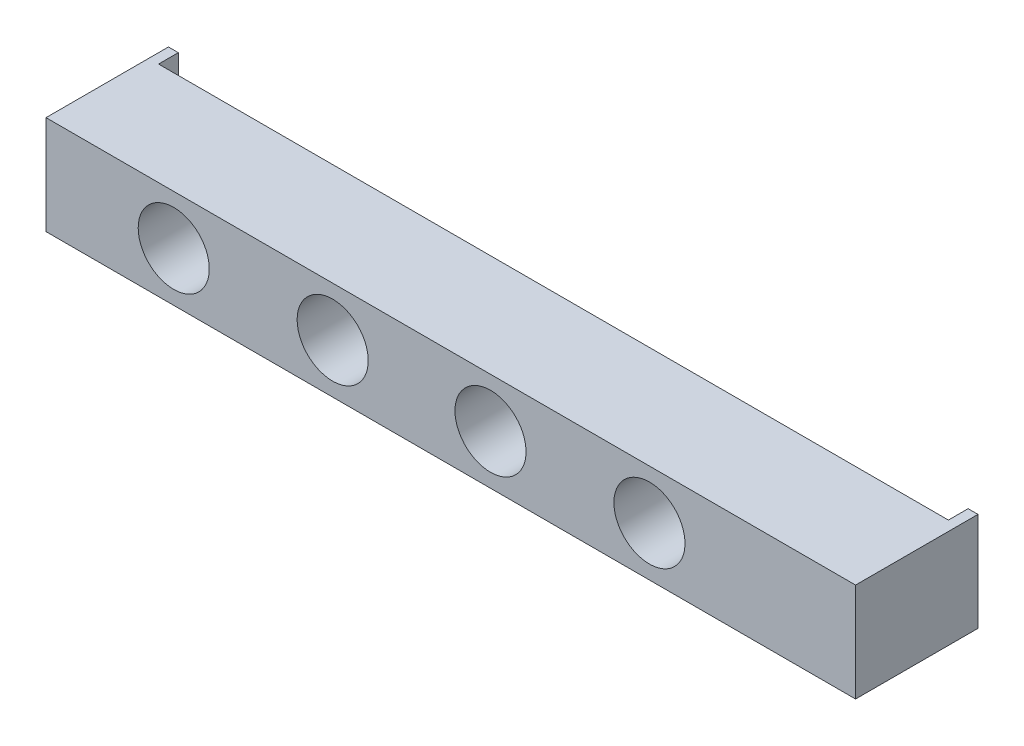
SolidWorks part; units mm, degrees
ref_plane "Ebene vorne" through (0, 0, 0) normal (0, 0, 1) x (1, 0, 0)
ref_plane "Ebene oben" through (0, 0, 0) normal (0, 1, 0) x (1, 0, 0)
ref_plane "Ebene rechts" through (0, 0, 0) normal (1, 0, 0) x (0, 0, -1)
sketch "Skizze1" plane through (0, 0, 0) normal (0, 0, 1) x (1, 0, 0)
  line L1 (0, 0) -> (205, 0)
  line L2 (0, 0) -> (0, 25)
  line L3 (0, 25) -> (205, 25)
  line L4 (205, 0) -> (205, 25)
  dimension "D1" = 205
  dimension "D2" = 25
extrude "Aufsatz-Linear austragen1" add sketch "Skizze1" along normal blind 26
sketch "Skizze2" plane through (0, 0, 0) normal (0, 0, -1) x (-1, 0, 0)
  line L0 (0, 0) -> (-205, 0) construction
  line L1 (0, 25) -> (-2.5, 25)
  line L2 (0, 25) -> (0, 0)
  line L3 (0, 0) -> (-2.5, 0)
  line L4 (-2.5, 25) -> (-2.5, 0)
  line L6 (-205, 25) -> (-202.5, 25)
  line L7 (-205, 25) -> (-205, 0)
  line L8 (-205, 0) -> (-202.5, 0)
  line L9 (-202.5, 25) -> (-202.5, 0)
  dimension "D1" = 2.5
  dimension "D2" = 2.5
extrude "Aufsatz-Linear austragen2" add sketch "Skizze2" along normal blind 5
sketch "Skizze12" plane through (0, 0, 0) normal (0, 0, -1) x (-1, 0, 0)
  line L0 (-22.5, -5.504) -> (-22.5, 41.1807) construction
  line L1 (-2.5, 25) -> (-2.5, 0) construction
  line L2 (-42.5, -5.504) -> (-42.5, 43.5606) construction
  line L3 (-62.5, -5.504) -> (-62.5, 45.2796) construction
  line L4 (-82.5, -5.504) -> (-82.5, 43.5606) construction
  line L5 (-102.5, -5.504) -> (-102.5, 45.2796) construction
  line L6 (-122.5, -5.504) -> (-122.5, 45.2796) construction
  line L7 (-142.5, -5.504) -> (-142.5, 45.2796) construction
  line L8 (-162.5, -5.504) -> (-162.5, 45.2796) construction
  dimension "D1" = 20
  dimension "D2" = 20
  dimension "D3" = 20
  dimension "D4" = 20
  dimension "D5" = 20
  dimension "D6" = 20
  dimension "D7" = 20
  dimension "D8" = 20
hole_wizard "Ø18.0 (18) Durchmesser Bohrung1" positions "Skizze13" profile "Skizze14" hole size "Ø18.0" standard "DIN" end condition through all
sketch "Skizze13" plane through (0, 0, 0) normal (0, 0, -1) x (-1, 0, 0)
  point P0 (-32.3443, 12.5)
  point P2 (-72.5887, 12.5)
  point P4 (-112.5611, 12.5)
  point P6 (-152.8054, 12.5)
sketch "Skizze14" plane through (32.3443, 12.5, 0) normal (1, 0, 0) x (0, 1, 0)
  line L0 (0, 0) -> (0, 26)
  line L1 (0, 26) -> (9, 26)
  line L2 (9, 26) -> (9, 0)
  line L5 (9, 0) -> (0, 0)
  line L11 (0, -6.35) -> (0, 107.95) construction
  dimension "Bohrerdurchmesser" = 18
  dimension "Bohrungstiefe" = 26
